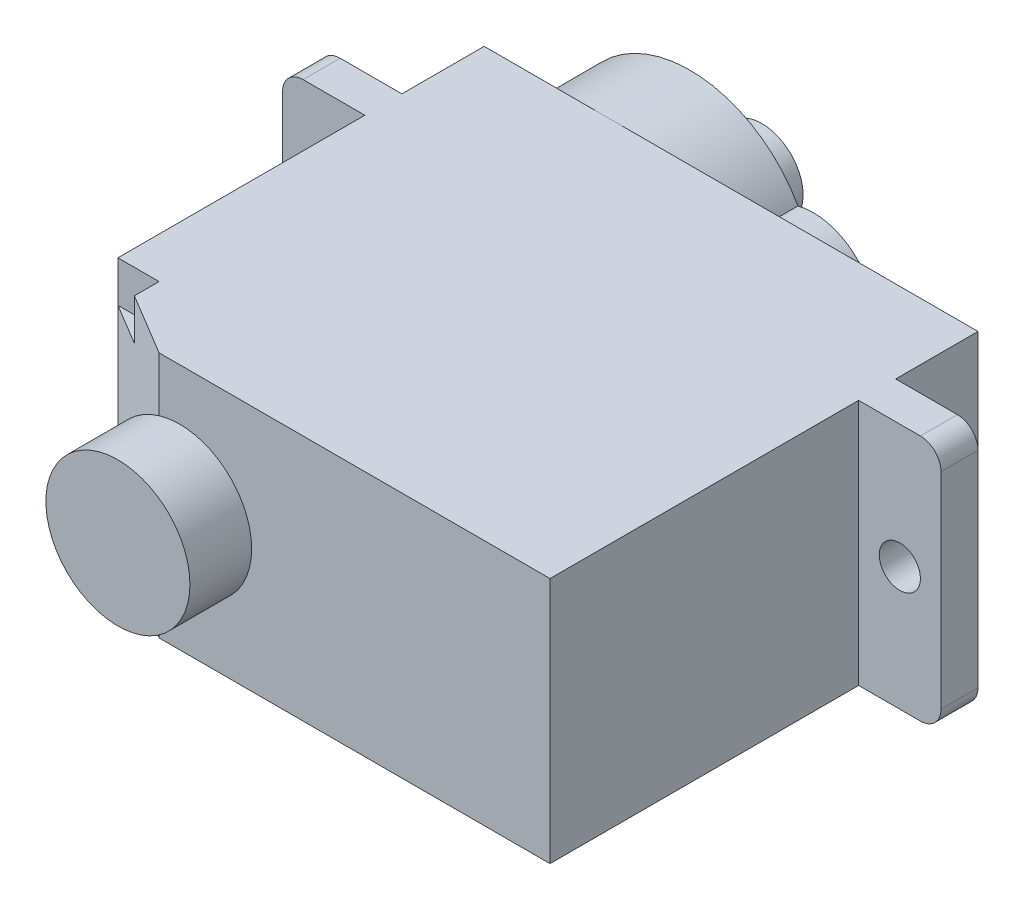
SolidWorks part; units mm, degrees
ref_plane "Спереди" through (0, 0, 0) normal (0, 0, 1) x (1, 0, 0)
ref_plane "Сверху" through (0, 0, 0) normal (0, 1, 0) x (1, 0, 0)
ref_plane "Справа" through (0, 0, 0) normal (1, 0, 0) x (0, 0, -1)
sketch "Эскиз1" plane through (0, 0, 0) normal (0, 0, 1) x (1, 0, 0)
  line L1 (-12, -6) -> (12, -6)
  line L2 (-12, -6) -> (-12, 6)
  line L3 (-12, 6) -> (12, 6)
  line L4 (12, -6) -> (12, 6)
  line L5 (-12, -6) -> (12, 6) construction
  line L6 (-12, 6) -> (12, -6) construction
  point P0 (0, 0)
extrude "Бобышка-Вытянуть1" add sketch "Эскиз1" along normal blind 12
sketch "Эскиз2" plane through (0, 0, 0) normal (0, 0, -1) x (-1, 0, 0)
  line L0 (12, 6) -> (15, 6)
  line L1 (12, -6) -> (15, -6)
  line L2 (16, -5) -> (16, 5)
  line L3 (-12, -6) -> (-15, -6)
  line L4 (-14, 0) -> (14, 0) construction
  line L6 (-12, 6) -> (-15, 6)
  line L7 (-16, 5) -> (-16, -5)
  line L8 (12, 6) -> (-12, 6)
  line L9 (12, -6) -> (-12, -6)
  arc A0 (-15, 6) -> (-16, 5) centre (-15, 5) ccw
  arc A1 (-15, -6) -> (-16, -5) centre (-15, -5) cw
  arc A2 (15, -6) -> (16, -5) centre (15, -5) ccw
  arc A3 (15, 6) -> (16, 5) centre (15, 5) cw
  circle A4 centre (14, 0) radius 1
  circle A5 centre (-14, 0) radius 1
  point P24 (0, 0)
  dimension "D1" = 1
extrude "Бобышка-Вытянуть2" add sketch "Эскиз2" along normal blind 1.8
sketch "Эскиз3" plane through (0, 0, -1.8) normal (0, 0, -1) x (-1, 0, 0)
  line L1 (-12, 6) -> (12, 6)
  line L2 (-12, 6) -> (-12, -6)
  line L3 (-12, -6) -> (12, -6)
  line L4 (12, 6) -> (12, -6)
  line L5 (-12, 6) -> (12, -6) construction
  line L6 (-12, -6) -> (12, 6) construction
  point P0 (0, 0)
extrude "Бобышка-Вытянуть3" add sketch "Эскиз3" along normal blind 4 contours L4 L3 L2 L1
sketch "Эскиз4" plane through (0, 0, -5.8) normal (0, 0, -1) x (-1, 0, 0)
  line L0 (12, 0) -> (6, 0) construction
  line L1 (12, 6) -> (12, -6) construction
  line L2 (0, 0) -> (-3, 0) construction
  circle A0 centre (6, 0) radius 6 construction
  arc A1 (0.75, -2.9047) -> (0.75, 2.9047) centre (0, 0) cw
  arc A2 (0.75, 2.9047) -> (0.75, -2.9047) centre (6, 0) cw
extrude "Бобышка-Вытянуть4" add sketch "Эскиз4" along normal blind 4 contours A2 A1
sketch "Эскиз5" plane through (0, 0, -9.8) normal (0, 0, -1) x (-1, 0, 0)
  circle A0 centre (6, 0) radius 2
extrude "Бобышка-Вытянуть5" add sketch "Эскиз5" along normal blind 3.5
sketch "Эскиз6" plane through (0, 0, 12) normal (0, 0, 1) x (1, 0, 0)
  line L0 (-12, 6) -> (-12, 4) construction
  line L4 (12, -6) -> (12, 6)
  line L5 (-12, -6) -> (12, 6) construction
  line L6 (-12, 6) -> (12, -6) construction
  line L7 (-12, 4) -> (-10, 4) construction
  line L8 (-10, 4) -> (-10, 6) construction
  line L9 (-12, -6) -> (-12, -4) construction
  line L10 (-12, -4) -> (-10, -4) construction
  line L11 (-10, -4) -> (-10, -6) construction
  line L12 (-10, -6) -> (-12, -6) construction
  line L13 (12, -6) -> (-10, -6)
  line L14 (-12, -4) -> (-12, 4)
  line L15 (-12, 4) -> (-10, 4)
  line L16 (-10, 4) -> (-10, 6)
  line L17 (-10, 6) -> (12, 6)
  line L18 (-10, -6) -> (-10, -4)
  line L19 (-10, -4) -> (-12, -4)
  point P4 (0, 0)
extrude "Бобышка-Вытянуть6" add sketch "Эскиз6" along normal blind 3
sketch "Эскиз8" plane through (0, 6, 0) normal (0, 1, 0) x (1, 0, 0)
  line L0 (-12, -12) -> (-7, -12) construction
  line L1 (-7, -12) -> (-7, -15) construction
  line L2 (12, -15) -> (-10, -15) construction
  line L3 (-7, -15) -> (-12, -12)
  line L4 (-12, -12) -> (-12, -15)
  line L5 (-12, -15) -> (-7, -15)
extrude "Вырез-Вытянуть1" cut sketch "Эскиз8" against normal blind 12
sketch "Эскиз9" plane through (0, 0, 15) normal (0, 0, 1) x (1, 0, 0)
  line L0 (-7, 0) -> (-6, 0) construction
  line L1 (-7, -6) -> (-7, 6) construction
  circle A0 centre (-6, 0) radius 3.5
extrude "Бобышка-Вытянуть7" add sketch "Эскиз9" along normal blind 3
